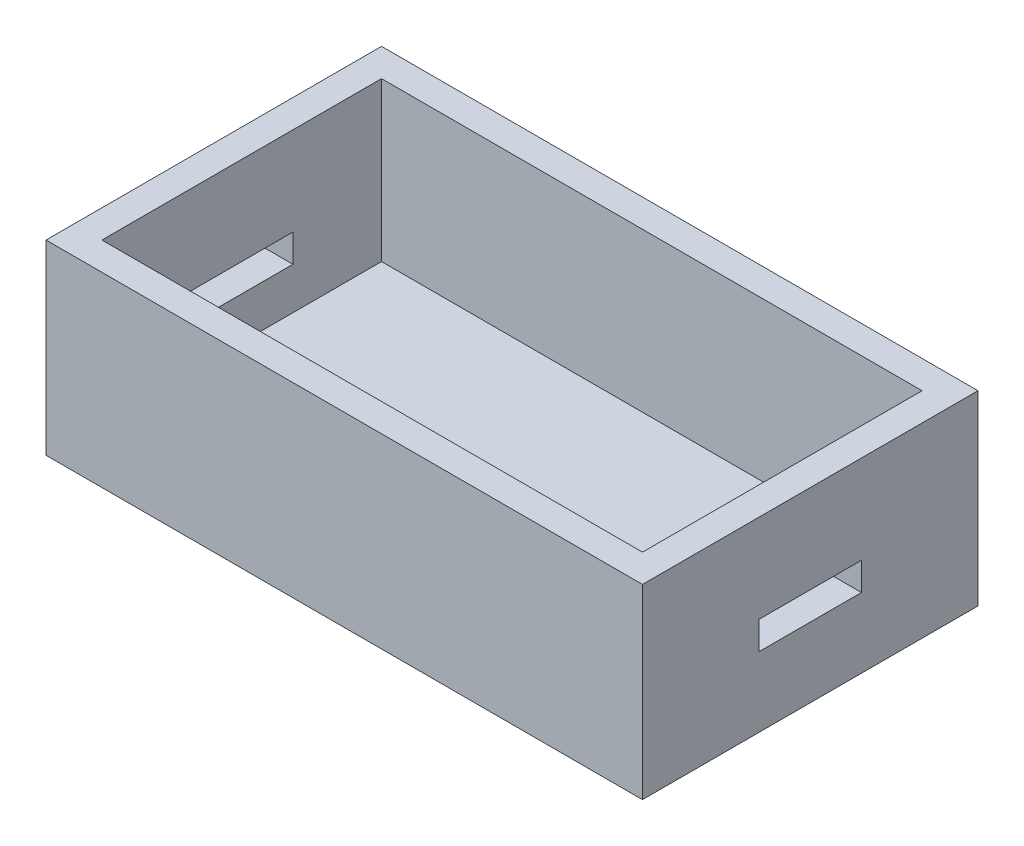
SolidWorks part; units mm, degrees
ref_plane "Front Plane" through (0, 0, 0) normal (0, 0, 1) x (1, 0, 0)
ref_plane "Top Plane" through (0, 0, 0) normal (0, 1, 0) x (1, 0, 0)
ref_plane "Right Plane" through (0, 0, 0) normal (1, 0, 0) x (0, 0, -1)
sketch "Sketch1" plane through (0, 0, 0) normal (0, 1, 0) x (1, 0, 0)
  line L1 (-16, -9) -> (16, -9)
  line L2 (-16, -9) -> (-16, 9)
  line L3 (-16, 9) -> (16, 9)
  line L4 (16, -9) -> (16, 9)
  line L5 (-16, -9) -> (16, 9) construction
  line L6 (-16, 9) -> (16, -9) construction
  point P0 (0, 0)
  dimension "D1" = 32
  dimension "D2" = 18
extrude "Boss-Extrude1" add sketch "Sketch1" along normal blind 10
shell "Shell1" thickness 1.5
sketch "Sketch3" plane through (16, 0, 0) normal (1, 0, 0) x (0, 0, -1)
  line L0 (-9, 10) -> (9, 10) construction
  line L1 (-2.75, 3.75) -> (2.75, 3.75)
  line L2 (-2.75, 3.75) -> (-2.75, 5.25)
  line L3 (-2.75, 5.25) -> (2.75, 5.25)
  line L4 (2.75, 3.75) -> (2.75, 5.25)
  line L5 (-2.75, 3.75) -> (2.75, 5.25) construction
  line L6 (-2.75, 5.25) -> (2.75, 3.75) construction
  line L7 (-9, 10) -> (-9, 0) construction
  point P0 (0, 4.5)
  dimension "D1" = 5.5
  dimension "D2" = 1.5
  dimension "D3" = 4.75
  dimension "D4" = 6.25
extrude "Cut-Extrude1" cut sketch "Sketch3" against normal through all
equation "\"length\"= 32mm"
equation "\"width\"= 18mm"
equation "\"height\"= 10mm"
equation "\"wall thickness\"= 1.5mm"
equation "\"bottom thickness\"= 1.5mm"
equation "\"clearance\"= 0.3mm"
equation "\"snap thickness\"= 1.2mm"
equation "\"snap length\"= 6mm"
equation "\"undercut\"= 0.5mm"
equation "\"radius\"= 0.8mm"
